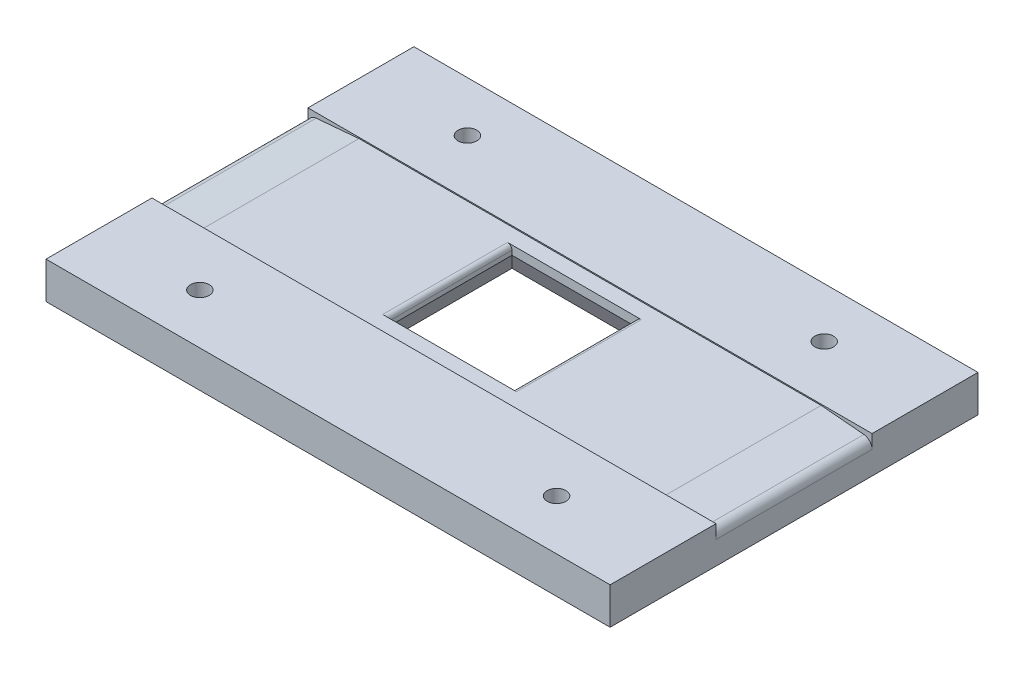
SolidWorks part; units mm, degrees
ref_plane "Спереди" through (0, 0, 0) normal (0, 0, 1) x (1, 0, 0)
ref_plane "Сверху" through (0, 0, 0) normal (0, 1, 0) x (1, 0, 0)
ref_plane "Справа" through (0, 0, 0) normal (1, 0, 0) x (0, 0, -1)
sketch "Эскиз1" plane through (0, 0, 0) normal (0, 1, 0) x (1, 0, 0)
  line L0 (-63.25, 41.25) -> (63.25, 41.25)
  line L1 (-63.25, -41.25) -> (63.25, -41.25)
  line L2 (14, 14) -> (-14, 14)
  line L4 (-63.25, -41.25) -> (-63.25, 41.25)
  line L5 (63.25, 41.25) -> (63.25, -41.25)
  line L6 (-14, 14) -> (-14, -14)
  line L7 (-14, -14) -> (14, -14)
  line L8 (14, -14) -> (14, 14)
extrude "Бобышка-Вытянуть1" add sketch "Эскиз1" along normal blind 8
ref_plane "Плоскость1" through (0, 8, 0) normal (0, 1, 0) x (1, 0, 0)
sketch "Эскиз2" plane through (0, 8, 0) normal (0, 1, 0) x (1, 0, 0)
  line L0 (-63.25, 17.5) -> (63.25, 17.5)
  line L2 (-63.25, 41.25) -> (-63.25, -41.25) construction
  line L3 (-63.25, 17.5) -> (-63.25, 41.25)
  line L4 (-63.25, 41.25) -> (63.25, 41.25)
  line L5 (63.25, 41.25) -> (63.25, 17.5)
  line L6 (63.25, -41.25) -> (63.25, 41.25) construction
  line L8 (-63.25, -17.5) -> (63.25, -17.5)
  line L9 (-63.25, -17.5) -> (-63.25, -41.25)
  line L10 (-63.25, -41.25) -> (63.25, -41.25)
  line L11 (63.25, -41.25) -> (63.25, -17.5)
extrude "Бобышка-Вытянуть2" add sketch "Эскиз2" along normal blind 0.25
chamfer "Фаска1" distance 1 angle 85 2 edges at (63.25, 8, 0) (-63.25, 8, 0)
fillet "Скругление1" radius 2 2 edges at (63.25, 7, 0) (-63.25, 7, 0)
fillet "Скругление2" radius 1 2 edges at (14, 8, 0) (-14, 8, 0)
sketch "Эскиз3" plane through (0, 8, 0) normal (0, 1, 0) x (1, 0, 0)
  circle A0 centre (-40, 30) radius 2.1
  circle A1 centre (40, 30) radius 2.1
  circle A2 centre (-40, -30) radius 2.1
  circle A3 centre (40, -30) radius 2.1
extrude "Вырез-Вытянуть1" cut sketch "Эскиз3" against normal through all both and the other way through all
chamfer "Фаска2" distance 6 angle 30 2 edges at (14, 0, 0) (-14, 0, 0)
chamfer "Фаска3" distance 6 angle 30 2 edges at (0, 0, 14) (0, 0, -14)
